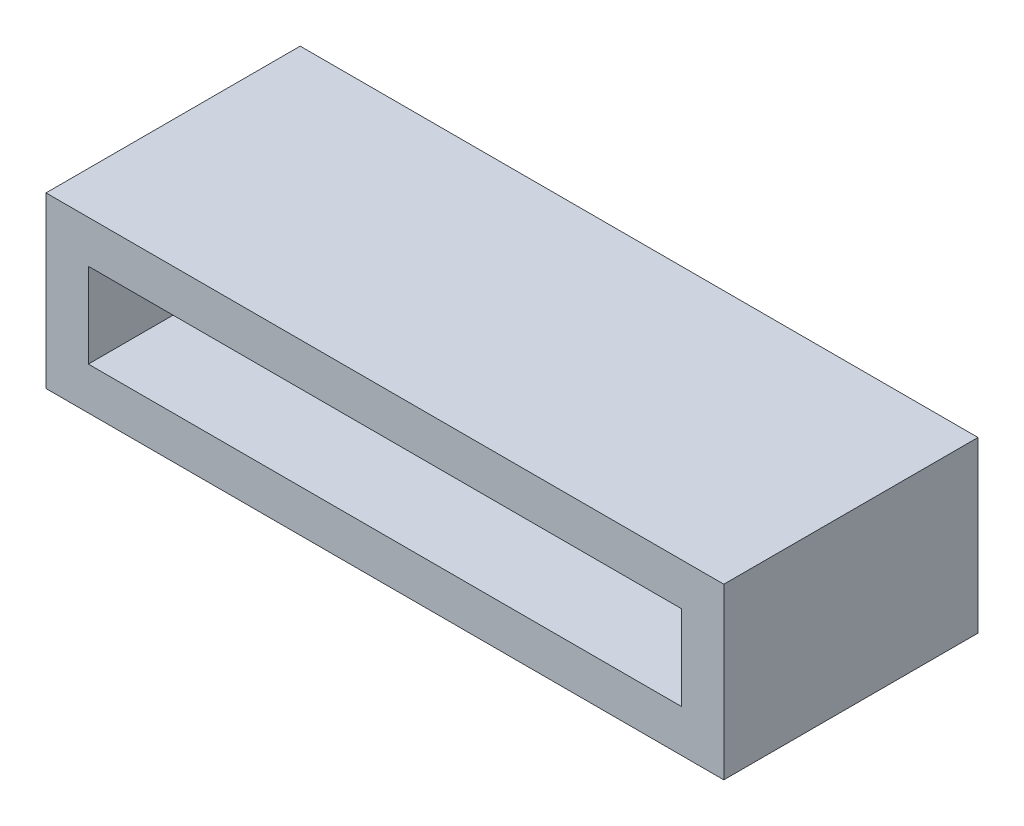
SolidWorks part; units mm, degrees
ref_plane "前视基准面" through (0, 0, 0) normal (0, 0, 1) x (1, 0, 0)
ref_plane "上视基准面" through (0, 0, 0) normal (0, 1, 0) x (1, 0, 0)
ref_plane "右视基准面" through (0, 0, 0) normal (1, 0, 0) x (0, 0, -1)
sketch "草图1" plane through (0, 0, 0) normal (0, 0, 1) x (1, 0, 0)
  line L0 (-7, 1) -> (7, 1)
  line L1 (-8, -2) -> (8, -2)
  line L2 (-8, -2) -> (-8, 2)
  line L3 (-8, 2) -> (8, 2)
  line L4 (8, -2) -> (8, 2)
  line L5 (-8, -2) -> (8, 2) construction
  line L6 (-8, 2) -> (8, -2) construction
  line L7 (7, -1) -> (7, 1)
  line L8 (-7, -1) -> (7, -1)
  line L9 (-7, -1) -> (-7, 1)
  point P0 (0, 0)
  dimension "D1" = 16
  dimension "D2" = 4
  dimension "D3" = 1
extrude "凸台-拉伸1" add sketch "草图1" along normal blind 6
